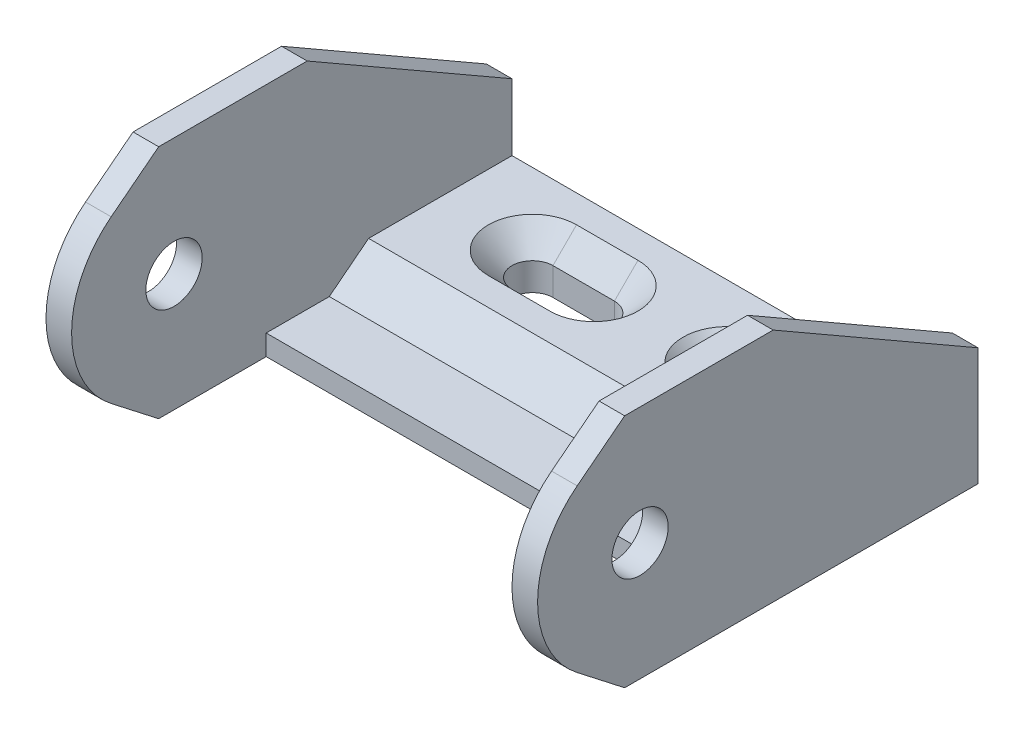
SolidWorks part; units mm, degrees
ref_plane "Front Plane" through (0, 0, 0) normal (0, 0, 1) x (1, 0, 0)
ref_plane "Top Plane" through (0, 0, 0) normal (0, 1, 0) x (1, 0, 0)
ref_plane "Right Plane" through (0, 0, 0) normal (1, 0, 0) x (0, 0, -1)
sketch "Sketch1" plane through (0, 0, 0) normal (1, 0, 0) x (0, 0, -1)
  line L0 (-17.25, 11.5) -> (-21.8873, 7.8951)
  line L1 (17.25, -11.5) -> (-17.25, -11.5)
  line L2 (17.25, -11.5) -> (17.25, 11.5)
  line L3 (17.25, 11.5) -> (-17.25, 11.5)
  line L4 (-17.25, -11.5) -> (-17.25, 11.5) construction
  line L5 (17.25, -11.5) -> (-17.25, 11.5) construction
  line L6 (17.25, 11.5) -> (-17.25, -11.5) construction
  line L7 (-21.8873, -7.8951) -> (-17.25, -11.5)
  line L8 (-21.8873, 7.8951) -> (-21.8873, -7.8951) construction
  arc A0 (-21.8873, 7.8951) -> (-21.8873, -7.8951) centre (-15.75, 0) ccw
  point P0 (0, 0)
  dimension "D2" = 10
  dimension "D4" = 43
  dimension "D1" = 1.5
  dimension "D3" = 23
extrude "Boss-Extrude1" add sketch "Sketch1" along normal mid plane 48
sketch "Sketch2" plane through (24, 0, 0) normal (1, 0, 0) x (0, 0, -1)
  line L0 (17.25, 0) -> (-2.75, 11.5)
  line L1 (17.25, -11.5) -> (17.25, 11.5) construction
  line L2 (17.25, 11.5) -> (-17.25, 11.5) construction
  line L3 (-2.75, 11.5) -> (17.25, 11.5)
  line L4 (17.25, 11.5) -> (17.25, 0)
  circle A0 centre (-15.75, 0) radius 2.75
  dimension "D2" = 5.5
  dimension "D1" = 20
extrude "Cut-Extrude1" cut sketch "Sketch2" against normal blind 48
sketch "Sketch4" plane through (0, 0, 0) normal (1, 0, 0) x (0, 0, -1)
  line L0 (17.25, -11.5) -> (17.25, 0) construction
  line L1 (-2.75, 11.5) -> (17.25, 0) construction
  line L2 (-2.75, 11.5) -> (-17.25, 11.5) construction
  line L3 (-21.8873, -7.8951) -> (-17.25, -11.5) construction
  line L4 (-17.25, 11.5) -> (-21.8873, 7.8951) construction
  line L5 (17.25, -6.5) -> (17.25, 0)
  line L6 (-2.75, 11.5) -> (17.25, 0)
  line L7 (-2.75, 11.5) -> (-17.25, 11.5)
  line L8 (-21.8873, -7.8951) -> (-17.25, -11.5)
  line L9 (-17.25, 11.5) -> (-21.8873, 7.8951)
  line L10 (17.25, -6.5) -> (3.25, -6.5)
  line L11 (3.25, -6.5) -> (-0.5898, -9.5)
  line L12 (-0.5898, -9.5) -> (-6.75, -9.5)
  line L13 (-6.75, -9.5) -> (-6.75, -11.5)
  line L14 (-17.25, -11.5) -> (17.25, -11.5) construction
  line L15 (-17.25, -11.5) -> (-6.75, -11.5)
  arc A0 (-21.8873, 7.8951) -> (-21.8873, -7.8951) centre (-15.75, 0) ccw construction
  arc A1 (-21.8873, 7.8951) -> (-21.8873, -7.8951) centre (-15.75, 0) ccw
  dimension "D1" = 5
  dimension "D2" = 14
  dimension "D3" = 38
  dimension "D4" = 24
  dimension "D5" = 2
extrude "Cut-Extrude2" cut sketch "Sketch4" against normal mid plane 43
sketch "Sketch5" plane through (0, -6.5, 0) normal (0, 1, 0) x (1, 0, 0)
  line L0 (6.5, 10.25) -> (12.5, 10.25) construction
  line L1 (6.5, 12.25) -> (12.5, 12.25)
  line L2 (6.5, 8.25) -> (12.5, 8.25)
  line L3 (12.5, 10.25) -> (21.5, 10.25) construction
  line L4 (21.5, 3.25) -> (21.5, 17.25) construction
  arc A0 (6.5, 12.25) -> (6.5, 8.25) centre (6.5, 10.25) ccw
  arc A1 (12.5, 8.25) -> (12.5, 12.25) centre (12.5, 10.25) ccw
  point P2 (9.5, 10.25)
  dimension "D1" = 4
  dimension "D2" = 6
  dimension "D3" = 9.5
extrude "Cut-Extrude3" cut sketch "Sketch5" against normal through all
chamfer "Chamfer1" distance 2.3 angle 45 4 edges at (9.5, -6.5, -8.25) (14.5, -6.5, -10.25) (4.5, -6.5, -10.25) (9.5, -6.5, -12.25)
mirror "Mirror1" about plane through (0, 0, 0) normal (1, 0, 0) of "Chamfer1", "Cut-Extrude3"
